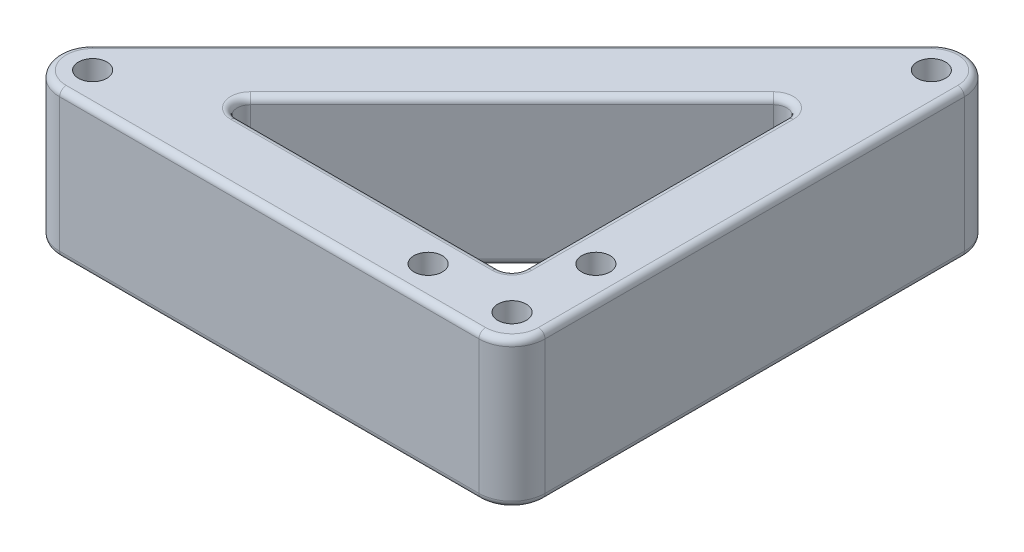
SolidWorks part; units mm, degrees
ref_plane "Front Plane" through (0, 0, 0) normal (0, 0, 1) x (1, 0, 0)
ref_plane "Top Plane" through (0, 0, 0) normal (0, 1, 0) x (1, 0, 0)
ref_plane "Right Plane" through (0, 0, 0) normal (1, 0, 0) x (0, 0, -1)
sketch "Sketch1" plane through (0, 0, 0) normal (0, 1, 0) x (1, 0, 0)
  line L0 (0, 0) -> (63.5, 63.5) construction
  line L1 (0, 0) -> (63.5, 0) construction
  line L2 (0, 0) -> (0, 63.5) construction
  line L3 (0, 63.5) -> (63.5, 63.5) construction
  line L4 (63.5, 0) -> (63.5, 63.5) construction
  line L5 (0, 0) -> (63.5, 63.5) construction
  line L6 (-3.5355, 3.5355) -> (59.9645, 67.0355)
  line L7 (3.5355, -3.5355) -> (67.0355, 59.9645)
  line L8 (0, -5) -> (68.5, -5)
  line L9 (68.5, 63.5) -> (68.5, -5)
  line L10 (0, 5) -> (58.5, 5)
  line L11 (58.5, 63.5) -> (58.5, 5)
  circle A0 centre (0, 0) radius 2.15
  circle A1 centre (63.5, 63.5) radius 2.15
  arc A2 (-3.5355, 3.5355) -> (3.5355, -3.5355) centre (0, 0) ccw
  arc A3 (67.0355, 59.9645) -> (59.9645, 67.0355) centre (63.5, 63.5) ccw
  circle A4 centre (63.5, 0) radius 2.15
  circle A5 centre (63.5, 63.5) radius 5 construction
  circle A6 centre (0, 0) radius 5 construction
  circle A7 centre (50.8, 0) radius 2.15
  circle A8 centre (63.5, 12.7) radius 2.15
  point P7 (31.75, 31.75)
  dimension "D2" = 4.3
  dimension "D3" = 5
  dimension "D1" = 63.5
  dimension "D4" = 12.7
  dimension "D5" = 12.7
extrude "Boss-Extrude1" add sketch "Sketch1" along normal blind 22.2504
fillet "Fillet1" radius 5 1 edges at (68.5, 11.1252, 5)
fillet "Fillet2" radius 2 3 edges at (58.5, 11.1252, -51.4289) (58.5, 11.1252, -5) (12.0711, 11.1252, -5)
fillet "Fillet3" radius 1 24 edges at (15.0517, 0, -6.2346) (36.6997, 0, -5) (57.9142, 0, -5.5858) (58.5, 0, -26.8003) (57.2654, 0, -48.4483) (-4.6194, 0, 1.9134) (28.2145, 0, -35.2855) (65.4134, 0, -68.1194) (68.5, 0, -31.75) (67.0355, 0, 3.5355) (15.0517, 22.2504, -6.2346) (35.2855, 22.2504, -28.2145) (57.2654, 22.2504, -48.4483) (58.5, 22.2504, -26.8003) (57.9142, 22.2504, -5.5858) (-4.6194, 22.2504, 1.9134) (28.2145, 22.2504, -35.2855) (65.4134, 22.2504, -68.1194) (68.5, 22.2504, -31.75) (67.0355, 22.2504, 3.5355) (35.2855, 0, -28.2145) (31.75, 0, 5) (36.6997, 22.2504, -5) (31.75, 22.2504, 5)
